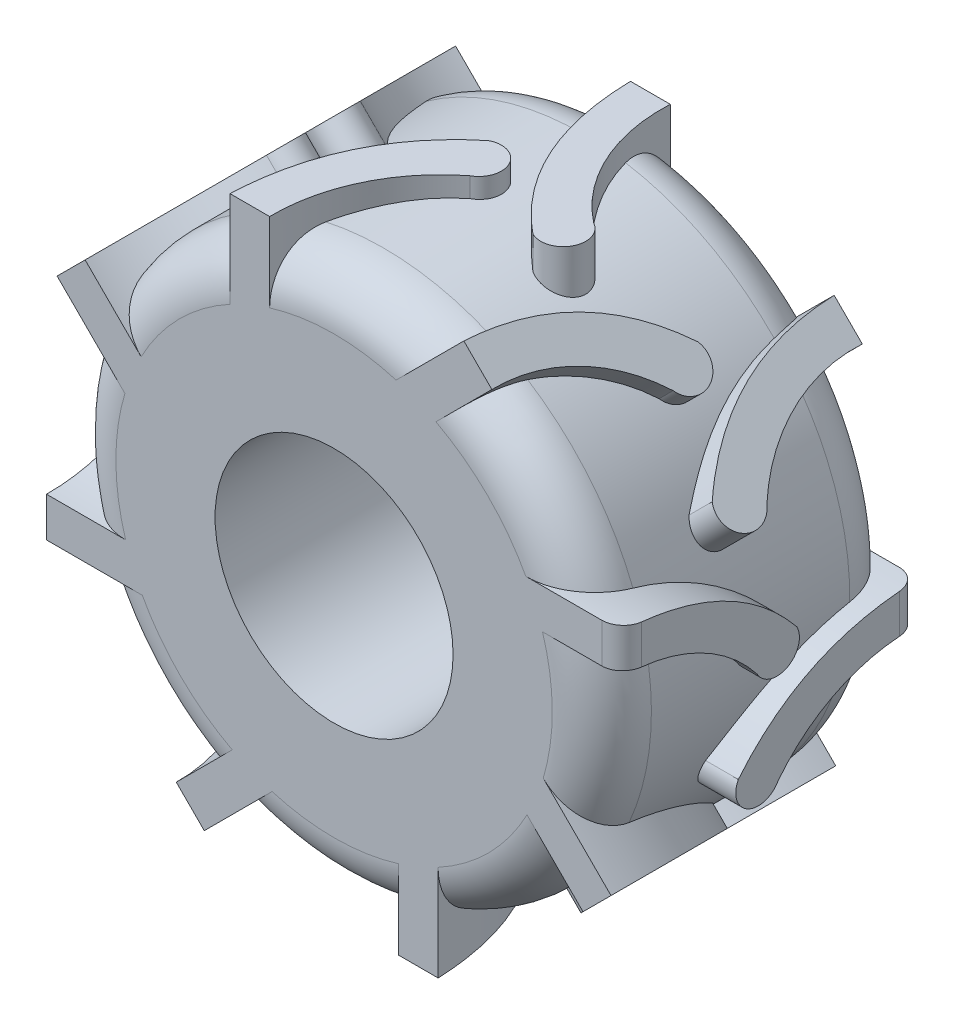
SolidWorks part; units mm, degrees
ref_plane "Alzado" through (0, 0, 0) normal (0, 0, 1) x (1, 0, 0)
ref_plane "Planta" through (0, 0, 0) normal (0, 1, 0) x (1, 0, 0)
ref_plane "Vista lateral" through (0, 0, 0) normal (1, 0, 0) x (0, 0, -1)
sketch "Sketch1" plane through (0, 0, 0) normal (0, 0, 1) x (1, 0, 0)
  circle A0 centre (0, 0) radius 27
  circle A1 centre (0, 0) radius 12
  dimension "D1" = 54
  dimension "D2" = 24
extrude "Boss-Extrude1" add sketch "Sketch1" along normal blind 30
fillet "Fillet1" radius 5 2 edges at (27, 0, 0) (27, 0, 30)
ref_plane "Plane1" through (29, 0, 0) normal (1, 0, 0) x (0, 0, -1)
sketch "Sketch2" plane through (29, 0, 0) normal (1, 0, 0) x (0, 0, -1)
  line L0 (-30, 10.4933) -> (-30, 6.4969)
  line L1 (-15, 27) -> (-15, -49973) construction
  line L2 (-5, 27) -> (-25, 27) construction
  line L3 (-30, 22) -> (-30, -22) construction
  line L6 (0, 0.1106) -> (0, -3.9015)
  line L7 (0, -22) -> (0, 22) construction
  arc A0 (-16.3376, -0.0409) -> (-12.3376, 2.0956) centre (-14.3464, 1.0439) ccw
  arc A1 (-30, 6.4969) -> (-16.3376, -0.0409) centre (-29.7212, -10.4651) cw
  arc A4 (-14.2362, -10.4236) -> (-18.2362, -8.2871) centre (-16.2274, -9.3388) cw
  arc A5 (0, -3.9015) -> (-14.2362, -10.4236) centre (-0.85, -20.8445) ccw
  spline S0 degree 2 poles (-12.3376, 2.0956) (-18.8437, 10.0394) (-30, 10.4933) knots 0 0 0 1 1 1
  spline S1 degree 2 poles (-18.2362, -8.2871) (-11.5464, -0.1236) (0, 0.1106) knots 0 0 0 1 1 1
  point P11 (-15, 27)
extrude "Boss-Extrude2" add sketch "Sketch2" against normal up to surface (23.1784 mm away)
fillet "Fillet2" radius 2 2 edges at (29, -1.8955, 0) (29, 8.4951, 30)
pattern_circular "CirPattern2" count 8 over 360 about axis through (0, 0, 30) along (0, 0, -1) of "Boss-Extrude2"
